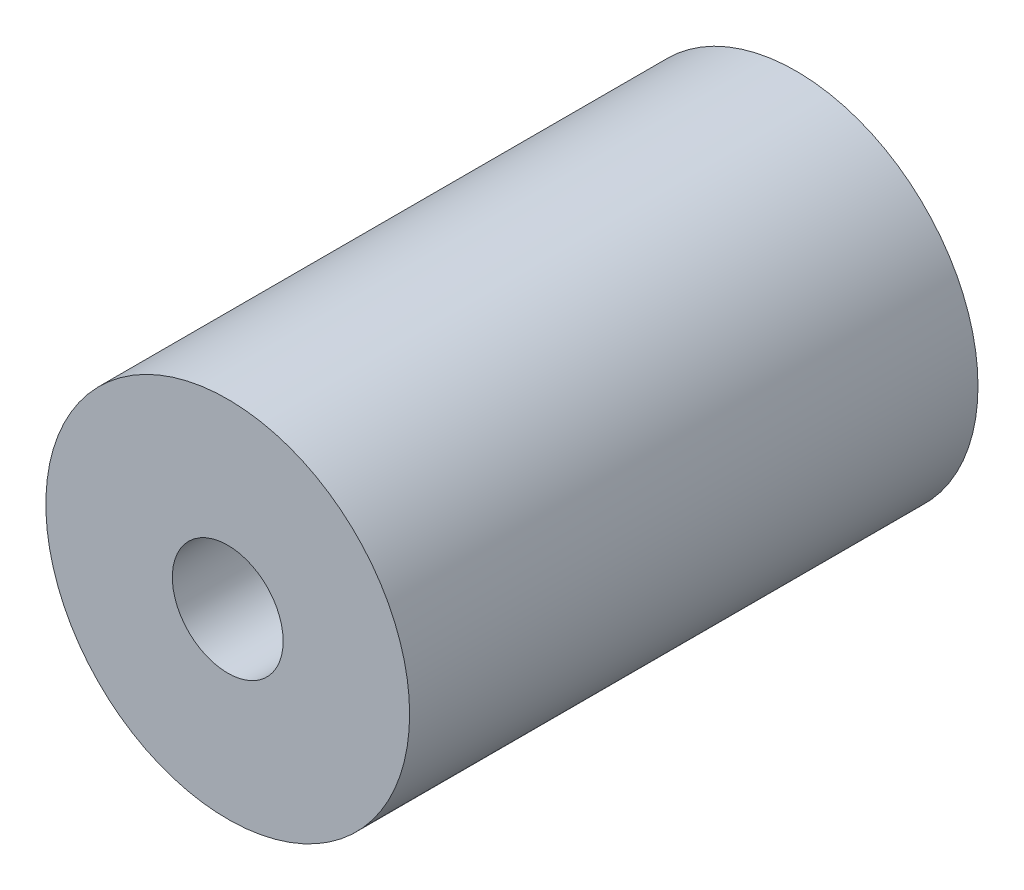
SolidWorks part; units mm, degrees
material "Brass"
ref_plane "Front Plane" through (0, 0, 0) normal (0, 0, 1) x (1, 0, 0)
ref_plane "Top Plane" through (0, 0, 0) normal (0, 1, 0) x (1, 0, 0)
ref_plane "Right Plane" through (0, 0, 0) normal (1, 0, 0) x (0, 0, -1)
sketch "Sketch1" plane through (0, 0, 0) normal (0, 0, 1) x (1, 0, 0)
  circle A0 centre (0, 0) radius 3.2
  circle A1 centre (0, 0) radius 0.975
  dimension "D1" = 6.4
  dimension "D2" = 1.95
extrude "Boss-Extrude1" add sketch "Sketch1" along normal blind 10
